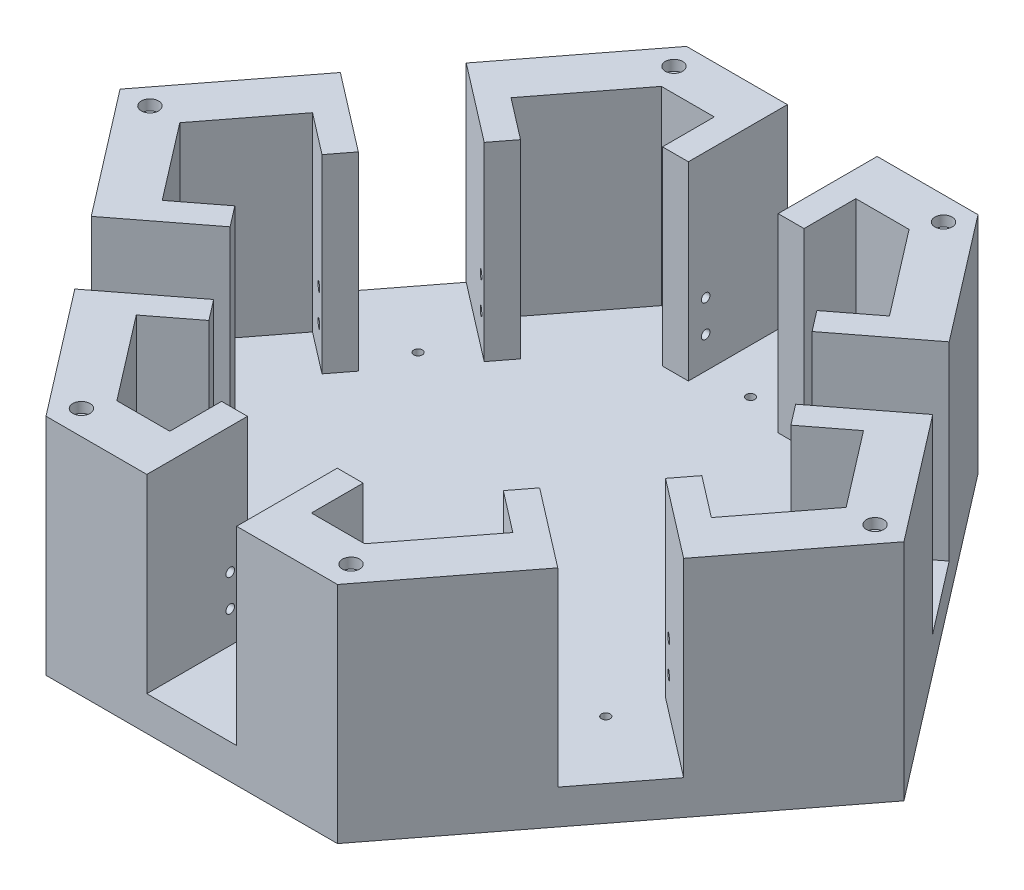
SolidWorks part; units mm, degrees
ref_plane "Front Plane" through (0, 0, 0) normal (0, 0, 1) x (1, 0, 0)
ref_plane "Top Plane" through (0, 0, 0) normal (0, 1, 0) x (1, 0, 0)
ref_plane "Right Plane" through (0, 0, 0) normal (1, 0, 0) x (0, 0, -1)
sketch "Sketch1" plane through (0, 0, 0) normal (0, 1, 0) x (1, 0, 0)
  line L0 (-42.4897, -94.35) -> (41.924, -94.35)
  line L1 (41.924, -94.35) -> (113.2397, -1.586)
  line L2 (113.2397, -1.586) -> (41.924, 91.178)
  line L3 (41.924, 91.178) -> (-42.4897, 91.178)
  line L4 (-42.4897, 91.178) -> (-113.8054, -1.586)
  line L5 (-113.8054, -1.586) -> (-42.4897, -94.35)
  point P2 (0, 0)
  point P7 (15.8192, -2.1893)
  point P8 (-6.942, -1.3823)
  point P9 (0, 0)
  dimension "D1" = 180
  dimension "D2" = 180
  dimension "D3" = 84.4137
  dimension "D4" = 117.0089
extrude "Boss-Extrude2" add sketch "Sketch1" along normal blind 65
sketch "Sketch4" plane through (-70.7629, 0, -54.4015) normal (-0.7928, 0, -0.6095) x (-0.6095, 0, 0.7928)
  line L0 (-46.3884, 65) -> (70.6205, 65) construction
  line L1 (-0.8839, 65) -> (25.1161, 65)
  line L2 (-0.8839, 65) -> (-0.8839, 10)
  line L3 (-0.8839, 10) -> (25.1161, 10)
  line L4 (25.1161, 65) -> (25.1161, 10)
  line L6 (-46.3884, 0) -> (70.6205, 0) construction
  dimension "D1" = 26
  dimension "D2" = 10
sketch "Sketch5" plane through (0, 65, 0) normal (0, 1, 0) x (1, 0, 0)
  line L6 (-96.7346, -1.3481) -> (-36.1162, 77.5013)
  line L7 (-36.1162, 77.5013) -> (35.6354, 77.5013)
  line L9 (35.6354, 77.5013) -> (96.2537, -1.3481)
  line L11 (96.2537, -1.3481) -> (35.6354, -80.1975)
  line L12 (35.6354, -80.1975) -> (-36.1162, -80.1975)
  line L13 (-36.1162, -80.1975) -> (-96.7346, -1.3481)
extrude "Cut-Extrude1" cut sketch "Sketch5" against normal blind 55
extrude "Cut-Extrude2" cut sketch "Sketch4" against normal blind 17
sketch "Sketch6" plane through (0, 0, -91.178) normal (0, 0, -1) x (-1, 0, 0)
  line L0 (-41.924, 65) -> (42.4897, 65) construction
  line L1 (-12.7172, 65) -> (13.2828, 65)
  line L2 (-12.7172, 65) -> (-12.7172, 10)
  line L3 (-12.7172, 10) -> (13.2828, 10)
  line L4 (13.2828, 65) -> (13.2828, 10)
  line L5 (42.4897, 0) -> (-41.924, 0) construction
  dimension "D1" = 10
  dimension "D2" = 26
sketch "Sketch7" plane through (70.4073, 0, -54.1282) normal (0.7928, 0, -0.6095) x (-0.6095, 0, -0.7928)
  line L0 (-70.2758, 65) -> (46.7332, 65) construction
  line L1 (-24.7713, 65) -> (1.2287, 65)
  line L2 (-24.7713, 65) -> (-24.7713, 10)
  line L3 (-24.7713, 10) -> (1.2287, 10)
  line L4 (1.2287, 65) -> (1.2287, 10)
  line L5 (68.1058, 0) -> (-48.9031, 0) construction
  dimension "D1" = 26
  dimension "D2" = 10
sketch "Sketch8" plane through (71.9401, 0, 55.3065) normal (0.7928, 0, 0.6095) x (0.6095, 0, -0.7928)
  line L0 (-49.2479, 65) -> (67.761, 65) construction
  line L1 (-3.7435, 65) -> (22.2565, 65)
  line L2 (-3.7435, 65) -> (-3.7435, 10)
  line L3 (-3.7435, 10) -> (22.2565, 10)
  line L4 (22.2565, 65) -> (22.2565, 10)
  line L5 (46.3884, 0) -> (-70.6205, 0) construction
  dimension "D1" = 26
  dimension "D2" = 10
sketch "Sketch9" plane through (0, 0, 94.35) normal (0, 0, 1) x (1, 0, 0)
  line L1 (-13.2828, 65) -> (12.7172, 65)
  line L2 (-13.2828, 65) -> (-13.2828, 10)
  line L3 (-13.2828, 10) -> (12.7172, 10)
  line L4 (12.7172, 65) -> (12.7172, 10)
sketch "Sketch10" plane through (-72.2956, 0, 55.5799) normal (-0.7928, 0, 0.6095) x (0.6095, 0, 0.7928)
  line L0 (-68.1058, 65) -> (48.9031, 65) construction
  line L1 (-22.6013, 65) -> (3.3987, 65)
  line L2 (-22.6013, 65) -> (-22.6013, 10)
  line L3 (-22.6013, 10) -> (3.3987, 10)
  line L4 (3.3987, 65) -> (3.3987, 10)
  line L5 (24.7713, 10) -> (-1.2287, 10) construction
  dimension "D1" = 26
extrude "Cut-Extrude3" cut sketch "Sketch10" against normal blind 17
extrude "Cut-Extrude4" cut sketch "Sketch9" against normal blind 17
extrude "Cut-Extrude5" cut sketch "Sketch8" against normal blind 17
extrude "Cut-Extrude6" cut sketch "Sketch7" against normal blind 17
extrude "Cut-Extrude7" cut sketch "Sketch6" against normal blind 17
sketch "Sketch11" plane through (0, 10, 0) normal (0, 1, 0) x (1, 0, 0)
  line L0 (35.6354, 77.5013) -> (12.7172, 77.5013) construction
  line L1 (-13.2828, -80.1975) -> (-20.7828, -80.1975)
  line L2 (-13.2828, -80.1975) -> (-13.2828, -65.1975)
  line L3 (-13.2828, -65.1975) -> (-20.7828, -65.1975)
  line L4 (-20.7828, -80.1975) -> (-20.7828, -65.1975)
  line L5 (12.7172, -80.1975) -> (20.2172, -80.1975)
  line L6 (12.7172, -80.1975) -> (12.7172, -65.1975)
  line L7 (12.7172, -65.1975) -> (20.2172, -65.1975)
  line L8 (20.2172, -80.1975) -> (20.2172, -65.1975)
  line L9 (-13.2828, 77.5013) -> (-20.7828, 77.5013)
  line L10 (-13.2828, 77.5013) -> (-13.2828, 62.5013)
  line L11 (-13.2828, 62.5013) -> (-20.7828, 62.5013)
  line L12 (-20.7828, 77.5013) -> (-20.7828, 62.5013)
  line L13 (20.2172, 77.5013) -> (12.7172, 77.5013)
  line L14 (20.2172, 77.5013) -> (20.2172, 62.5013)
  line L15 (20.2172, 62.5013) -> (12.7172, 62.5013)
  line L16 (12.7172, 77.5013) -> (12.7172, 62.5013)
  line L17 (-75.2265, -29.3247) -> (-63.3346, -20.1824)
  line L18 (-75.2265, -29.3247) -> (-86.0709, -37.6617) construction
  line L19 (-96.7346, -1.3481) -> (-75.2265, -29.3247) construction
  line L20 (-63.3346, -20.1824) -> (-67.9058, -14.2364)
  line L21 (-67.9058, -14.2364) -> (-79.7977, -23.3787)
  line L22 (-79.7977, -23.3787) -> (-75.2265, -29.3247)
  line L23 (-59.3798, -49.9373) -> (-47.4879, -40.795)
  line L24 (-47.4879, -40.795) -> (-42.9167, -46.741)
  line L25 (-42.9167, -46.741) -> (-54.8087, -55.8833)
  line L26 (-59.3798, -49.9373) -> (-36.1162, -80.1975) construction
  line L27 (-54.8087, -55.8833) -> (-59.3798, -49.9373)
  line L28 (-75.4565, 26.3294) -> (-63.5645, 17.1871)
  line L29 (-63.5645, 17.1871) -> (-68.1357, 11.2411)
  line L30 (-68.1357, 11.2411) -> (-80.0276, 20.3835)
  line L31 (-75.4565, 26.3294) -> (-96.7346, -1.3481) construction
  line L32 (-80.0276, 20.3835) -> (-75.4565, 26.3294)
  line L33 (-59.6097, 46.9421) -> (-47.7178, 37.7997)
  line L34 (-36.1162, 77.5013) -> (-59.6097, 46.9421) construction
  line L35 (-59.6097, 46.9421) -> (-70.2242, 55.1023) construction
  line L36 (-47.7178, 37.7997) -> (-43.1466, 43.7457)
  line L37 (-43.1466, 43.7457) -> (-55.0386, 52.888)
  line L38 (-55.0386, 52.888) -> (-59.6097, 46.9421)
  line L39 (58.8675, -49.9783) -> (46.9755, -40.836)
  line L40 (46.9755, -40.836) -> (42.4044, -46.782)
  line L41 (42.4044, -46.782) -> (54.2963, -55.9243)
  line L42 (54.2963, -55.9243) -> (58.8675, -49.9783)
  line L43 (74.7142, -29.3657) -> (62.8223, -20.2234)
  line L44 (62.8223, -20.2234) -> (67.3934, -14.2774)
  line L45 (67.3934, -14.2774) -> (79.2854, -23.4197)
  line L46 (79.2854, -23.4197) -> (74.7142, -29.3657)
  line L47 (74.9441, 26.3704) -> (63.0522, 17.2281)
  line L48 (63.0522, 17.2281) -> (67.6233, 11.2821)
  line L49 (67.6233, 11.2821) -> (79.5153, 20.4245)
  line L50 (96.2537, -1.3481) -> (74.9441, 26.3704) construction
  line L51 (79.5153, 20.4245) -> (74.9441, 26.3704)
  line L52 (59.0974, 46.9831) -> (47.2055, 37.8407)
  line L53 (47.2055, 37.8407) -> (42.6343, 43.7867)
  line L54 (42.6343, 43.7867) -> (54.5262, 52.929)
  line L55 (59.0974, 46.9831) -> (35.6354, 77.5013) construction
  line L56 (54.5262, 52.929) -> (59.0974, 46.9831)
  line L57 (74.7142, -29.3657) -> (96.2537, -1.3481) construction
  line L58 (35.6354, -80.1975) -> (58.8675, -49.9783) construction
  line L60 (58.8675, -49.9783) -> (69.6585, -58.2743) construction
  line L61 (-75.4565, 26.3294) -> (-86.0709, 34.4897) construction
  line L62 (12.7172, 77.5013) -> (12.7172, 91.178) construction
  line L67 (-75.2265, -29.3247) -> (-86.0709, -37.6617) construction
  dimension "D1" = 7.5
  dimension "D2" = 15
  dimension "D3" = 180
  dimension "D4" = 180
extrude "Boss-Extrude4" add sketch "Sketch11" along normal blind 55
sketch "Sketch12" plane through (0, 10, 0) normal (0, 1, 0) x (1, 0, 0)
  line L1 (12.7172, -65.1975) -> (12.7172, -94.35) construction
  line L2 (-63.3346, -20.1824) -> (-86.0709, -37.6617) construction
  line L3 (-63.3346, -20.1824) -> (-67.9058, -14.2364) construction
  line L4 (-47.7178, 37.7997) -> (-70.2242, 55.1023) construction
  line L5 (-47.7178, 37.7997) -> (-43.1466, 43.7457) construction
  line L6 (12.7172, 62.5013) -> (12.7172, 91.178) construction
  line L7 (12.7172, 62.5013) -> (20.2172, 62.5013) construction
  line L8 (63.0522, 17.2281) -> (85.5052, 34.4897) construction
  line L9 (63.0522, 17.2281) -> (67.6233, 11.2821) construction
  line L10 (46.9755, -40.836) -> (69.6585, -58.2743) construction
  line L11 (46.9755, -40.836) -> (42.4044, -46.782) construction
  circle A0 centre (-0.2828, -70.1975) radius 1.25
  circle A1 centre (-59.3752, -33.5361) radius 1.25
  circle A2 centre (-59.6051, 30.5409) radius 1.25
  circle A3 centre (-0.2828, 67.5013) radius 1.25
  circle A4 centre (59.0928, 30.5819) radius 1.25
  circle A5 centre (58.8629, -33.5771) radius 1.25
  point P29 (0, 0)
  point P31 (61.8834, 25.5328)
  dimension "D3" = 2.5
  dimension "D4" = 2.5
  dimension "D7" = 2.5
  dimension "D8" = 13
  dimension "D1" = 13
  dimension "D2" = 5
  dimension "D5" = 13
  dimension "D6" = 5
  dimension "D9" = 5
  dimension "D10" = 13
  dimension "D11" = 5
  dimension "D12" = 13
  dimension "D13" = 5
  dimension "D14" = 13
  dimension "D15" = 5
extrude "Cut-Extrude8" cut sketch "Sketch12" against normal blind 17
sketch "Sketch13" plane through (-13.2828, 0, 0) normal (1, 0, 0) x (0, 0, -1)
  line L0 (62.5013, 10) -> (91.178, 10) construction
  line L1 (62.5013, 65) -> (62.5013, 10) construction
  circle A0 centre (67.5013, 28.4) radius 1.25
  circle A1 centre (67.5013, 19.2) radius 1.25
  point P6 (0, 0)
  point P7 (0, 0)
  point P8 (0, 0)
  point P9 (69.1976, 19.2)
  point P10 (0, 0)
  dimension "D1" = 2.5
  dimension "D2" = 2.5
  dimension "D3" = 9.2
  dimension "D4" = 18.4
  dimension "D5" = 5
extrude "Cut-Extrude9" cut sketch "Sketch13" against normal blind 11
sketch "Sketch14" plane through (12.7172, 0, 0) normal (-1, 0, 0) x (0, 0, 1)
  line L0 (-62.5013, 65) -> (-62.5013, 10) construction
  line L1 (-62.5013, 10) -> (-91.178, 10) construction
  circle A0 centre (-67.5013, 19.2) radius 1.25
  circle A1 centre (-67.5013, 26.8245) radius 1.25
  point P8 (0, 0)
  dimension "D4" = 2.5
  dimension "D1" = 5
  dimension "D2" = 9.2
  dimension "D3" = 16.8245
extrude "Cut-Extrude10" cut sketch "Sketch14" against normal blind 11
sketch "Sketch15" plane through (-5.3201, 0, -6.9201) normal (-0.6095, 0, -0.7928) x (-0.7928, 0, 0.6095)
  line L0 (-75.4877, 10) -> (-60.4877, 10) construction
  line L1 (-60.4877, 65) -> (-60.4877, 10) construction
  circle A0 centre (-65.4877, 19.2) radius 1.25
  circle A1 centre (-65.4877, 28.4) radius 1.25
  point P8 (0, 0)
  dimension "D4" = 2.5
  dimension "D1" = 9.2
  dimension "D2" = 18.4
  dimension "D3" = 5
extrude "Cut-Extrude11" cut sketch "Sketch15" against normal blind 43
sketch "Sketch16" plane through (18.1363, 0, -23.5908) normal (0.6095, 0, -0.7928) x (-0.7928, 0, -0.6095)
  line L0 (-77.1311, 10) -> (-62.1311, 10) construction
  line L1 (-62.1311, 65) -> (-62.1311, 10) construction
  circle A0 centre (-67.1311, 28.4) radius 1.25
  circle A1 centre (-67.1311, 19.2) radius 1.25
  point P8 (0, 0)
  point P9 (0, 0)
  dimension "D1" = 2.5
  dimension "D2" = 9.2
  dimension "D3" = 18.4
  dimension "D4" = 5
extrude "Cut-Extrude12" cut sketch "Sketch16" against normal blind 43
sketch "Sketch17" plane through (-20.7828, 0, 0) normal (-1, 0, 0) x (0, 0, 1)
  line L0 (65.1975, 10) -> (80.1975, 10) construction
  line L1 (65.1975, 65) -> (65.1975, 10) construction
  circle A0 centre (70.1975, 19.2) radius 1.25
  circle A1 centre (70.1975, 28.4) radius 1.25
  point P6 (0, 0)
  point P8 (68.7495, 19.737)
  point P10 (0, 0)
  dimension "D1" = 2.5
  dimension "D2" = 18.4
  dimension "D3" = 9.2
  dimension "D4" = 5
extrude "Cut-Extrude13" cut sketch "Sketch17" against normal blind 43
sketch "Sketch18" plane through (6.6426, 0, 8.6404) normal (0.6095, 0, 0.7928) x (0.7928, 0, -0.6095)
  line L0 (-77.5123, 10) -> (-62.5123, 10) construction
  line L1 (-62.5123, 65) -> (-62.5123, 10) construction
  circle A0 centre (-67.5123, 19.2) radius 1.25
  circle A1 centre (-67.5123, 28.4) radius 1.25
  point P8 (0, 0)
  point P9 (0, 0)
  dimension "D4" = 2.5
  dimension "D1" = 9.2
  dimension "D2" = 18.4
  dimension "D3" = 5
extrude "Cut-Extrude14" cut sketch "Sketch18" against normal blind 43
sketch "Sketch19" plane through (5.1099, 0, -6.6467) normal (0.6095, 0, -0.7928) x (-0.7928, 0, -0.6095)
  line L0 (60.8689, 10) -> (75.8689, 10) construction
  line L1 (60.8689, 65) -> (60.8689, 10) construction
  circle A0 centre (65.8689, 19.2) radius 1.25
  circle A1 centre (65.8689, 28.4) radius 1.25
  point P8 (0, 0)
  dimension "D3" = 2.5
  dimension "D1" = 9.2
  dimension "D2" = 18.4
  dimension "D4" = 5
extrude "Cut-Extrude15" cut sketch "Sketch19" against normal blind 43
sketch "Sketch20" plane through (0, 65, 0) normal (0, 1, 0) x (1, 0, 0)
  circle A0 centre (104.7467, -1.4671) radius 2.5
  circle A1 centre (38.7797, 84.3396) radius 2.5
  circle A2 centre (-39.303, 84.3396) radius 2.5
  circle A3 centre (-105.27, -1.4671) radius 2.5
  circle A4 centre (-39.303, -87.2737) radius 2.5
  circle A5 centre (38.7797, -87.2737) radius 2.5
  point P34 (38.7797, -87.2737)
  point P35 (-39.303, -87.2737)
  point P36 (-105.27, -1.4671)
  point P37 (-39.303, 84.3396)
  point P38 (38.7797, 84.3396)
  dimension "D1" = 5
extrude "Cut-Extrude16" cut sketch "Sketch20" against normal blind 3
